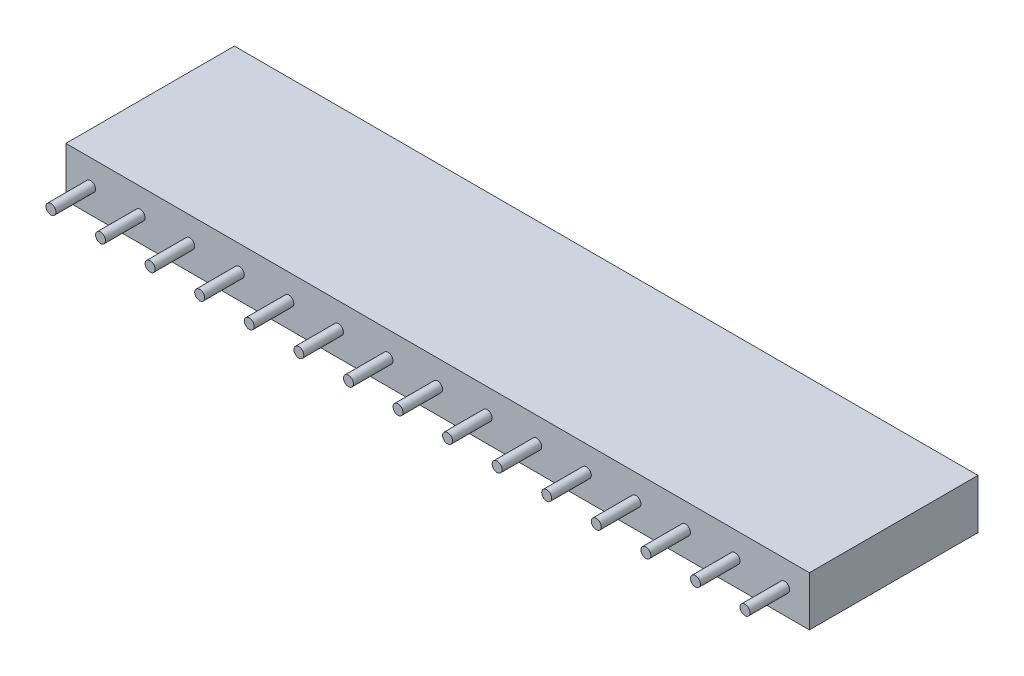
SolidWorks part; units mm, degrees
ref_plane "Plan de face" through (0, 0, 0) normal (0, 0, 1) x (1, 0, 0)
ref_plane "Plan de dessus" through (0, 0, 0) normal (0, 1, 0) x (1, 0, 0)
ref_plane "Plan de droite" through (0, 0, 0) normal (1, 0, 0) x (0, 0, -1)
sketch "Esquisse1" plane through (0, 0, 0) normal (0, 0, 1) x (1, 0, 0)
  line L1 (0, 0) -> (-2.5, 0)
  line L2 (0, 0) -> (0, 2.5)
  line L3 (0, 2.5) -> (-2.5, 2.5)
  line L4 (-2.5, 0) -> (-2.5, 2.5)
  dimension "D1" = 2.5
  dimension "D2" = 2.5
extrude "Boss.-Extru.1" add sketch "Esquisse1" along normal blind 8.5
sketch "Esquisse2" plane through (0, 0, 8.5) normal (0, 0, 1) x (1, 0, 0)
  line L0 (-2.5, 2.5) -> (0, 0) construction
  circle A0 centre (-1.25, 1.25) radius 0.25
  dimension "D1" = 0.5
extrude "Boss.-Extru.2" add sketch "Esquisse2" along normal blind 2
sketch "Esquisse3" plane through (0, 0, 0) normal (0, 0, -1) x (-1, 0, 0)
  line L0 (0, 2.5) -> (2.5, 0) construction
  circle A0 centre (1.25, 1.25) radius 0.25
  dimension "D1" = 0.5
extrude "Enlèv. mat.-Extru.2" cut sketch "Esquisse3" against normal blind 4
pattern_linear "Répétition linéaire1" count 15 spacing 2.5 along (-1, 0, 0) of "Boss.-Extru.1", "Enlèv. mat.-Extru.2", "Boss.-Extru.2"
